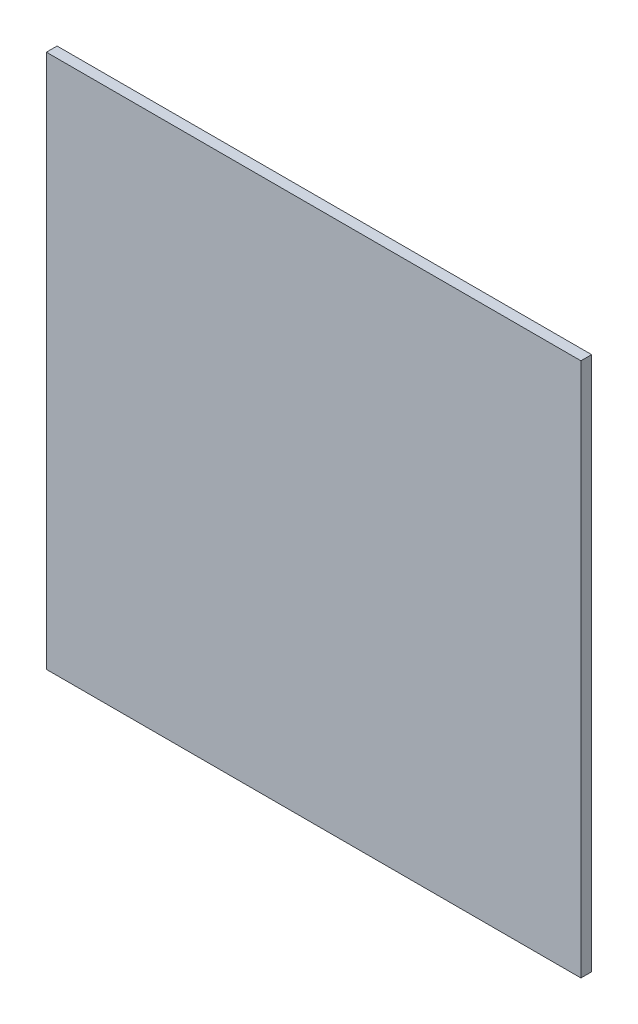
SolidWorks part; units mm, degrees
ref_plane "Plan de face" through (0, 0, 0) normal (0, 0, 1) x (1, 0, 0)
ref_plane "Plan de dessus" through (0, 0, 0) normal (0, 1, 0) x (1, 0, 0)
ref_plane "Plan de droite" through (0, 0, 0) normal (1, 0, 0) x (0, 0, -1)
sketch "Esquisse1" plane through (0, 0, 0) normal (0, 0, 1) x (1, 0, 0)
  line L1 (-250, 250) -> (250, 250)
  line L2 (-250, 250) -> (-250, -250)
  line L3 (-250, -250) -> (250, -250)
  line L4 (250, 250) -> (250, -250)
  line L5 (-250, 250) -> (250, -250) construction
  line L6 (-250, -250) -> (250, 250) construction
  point P0 (0, 0)
  dimension "D1" = 500
  dimension "D2" = 500
extrude "Boss.-Extru.1" add sketch "Esquisse1" along normal blind 10
